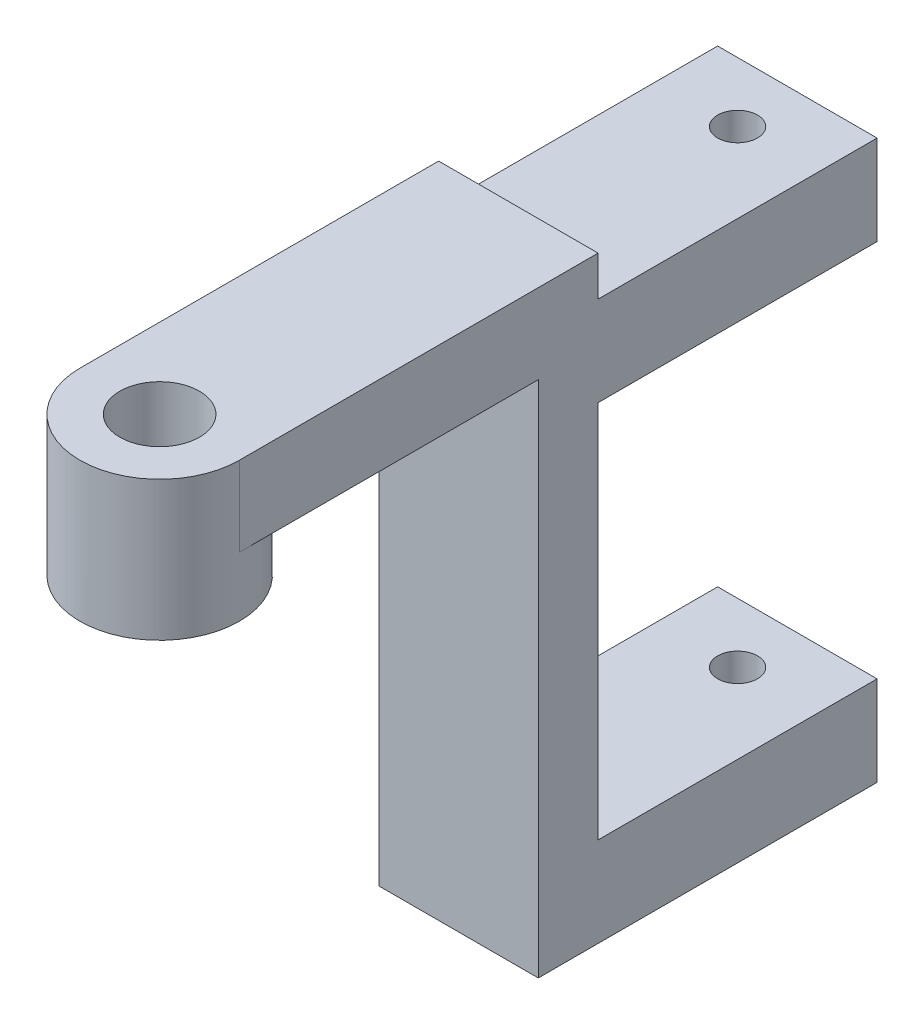
SolidWorks part; units mm, degrees
ref_plane "前视基准面" through (0, 0, 0) normal (0, 0, 1) x (1, 0, 0)
ref_plane "上视基准面" through (0, 0, 0) normal (0, 1, 0) x (1, 0, 0)
ref_plane "右视基准面" through (0, 0, 0) normal (1, 0, 0) x (0, 0, -1)
other "Configuration Table"
sketch "草图1" plane through (0, 0, 0) normal (0, 1, 0) x (1, 0, 0)
  circle A0 centre (0, 0) radius 2
  dimension "D1" = 4
extrude "拉伸-薄壁1" add sketch "草图1" along normal blind 3 thin
sketch "草图2" plane through (0, 3, 0) normal (0, 1, 0) x (1, 0, 0)
  circle A0 centre (0, 0) radius 4
  circle A1 centre (0, 0) radius 4
  circle A2 centre (0, 0) radius 4
  circle M2 centre (0, 0) radius 4
  circle M3 centre (0, 0) radius 2
  dimension "D1" = 0
extrude "凸台-拉伸1" add sketch "草图2" along normal blind 2 contours M2 M3 | M3
sketch "草图3" plane through (0, 5, 0) normal (0, 1, 0) x (1, 0, 0)
  line L1 (-4, 15) -> (4, 15)
  line L2 (-4, 15) -> (-4, 0)
  line L3 (-4, 0) -> (4, 0)
  line L4 (4, 15) -> (4, 0)
  circle A1 centre (0, 0) radius 4
  circle A2 centre (0, 0) radius 4
  circle M6 centre (0, 0) radius 4
  dimension "D2" = 15
  dimension "D1" = 0
extrude "凸台-拉伸2" add sketch "草图3" along normal blind 2 and the other way blind 2 contours L3 M6 | L3 M6 | L4 L1 L2 M6
sketch "草图4" plane through (0, 0, -15) normal (0, 0, -1) x (-1, 0, 0)
  line L1 (-4, 7) -> (4, 7)
  line L2 (-4, 7) -> (-4, -23)
  line L3 (-4, -23) -> (4, -23)
  line L4 (4, 3) -> (4, 7)
  line L5 (4, 7) -> (-4, 7)
  line L6 (-4, 7) -> (-4, 3)
  line L7 (-4, 3) -> (4, 3)
  line L8 (4, 3) -> (4, 7)
  line L9 (4, 7) -> (-4, 7)
  line L10 (-4, 7) -> (-4, 3)
  line L11 (-4, 3) -> (4, 3)
  line L12 (4, 7) -> (4, -23)
  line M9 (4, 3) -> (4, 7)
  line M10 (4, 7) -> (-4, 7)
  line M11 (-4, 7) -> (-4, 3)
  line M12 (-4, 3) -> (4, 3)
  dimension "D2" = 30
  dimension "D1" = 0
extrude "凸台-拉伸3" add sketch "草图4" along normal blind 3 contours L12 L2 L3 M12 | M12 M9 M10 M11
sketch "草图5" plane through (0, 0, -18) normal (0, 0, -1) x (-1, 0, 0)
  line L0 (-16.8506, -9) -> (14.6334, -9) construction
  line L2 (-9.5, 0.5) -> (9.5, 0.5)
  line L3 (-9.5, 0.5) -> (-9.5, -18.5)
  line L4 (4, -23) -> (4, 7)
  line L5 (4, 7) -> (-4, 7)
  line L6 (-4, 7) -> (-4, -23)
  line L7 (-4, -23) -> (4, -23)
  line L8 (4, -23) -> (4, 7)
  line L9 (4, 7) -> (-4, 7)
  line L10 (-4, 7) -> (-4, -23)
  line L11 (-4, -23) -> (4, -23)
  line L12 (-9.5, -18.5) -> (9.5, -18.5)
  line L13 (9.5, 0.5) -> (9.5, -18.5)
  line L14 (-9.5, 0.5) -> (9.5, -18.5) construction
  line L15 (-9.5, -18.5) -> (9.5, 0.5) construction
  line L16 (-4, -23) -> (4, -23)
  line L17 (-4, -23) -> (-4, -18.5)
  line L18 (-4, -18.5) -> (4, -18.5)
  line L19 (4, -23) -> (4, -18.5)
  line L20 (-4, 5) -> (4, 5)
  line L21 (-4, 5) -> (-4, 0.5)
  line L22 (-4, 0.5) -> (4, 0.5)
  line L23 (4, 5) -> (4, 0.5)
  point P6 (0, -9)
  line M14 (4, -23) -> (4, 7)
  line M17 (-4, -23) -> (4, -23)
  dimension "D2" = 16
  dimension "D3" = 19
  dimension "D4" = 19
  dimension "D5" = 4.5
  dimension "D6" = 4.5
  dimension "D1" = 0
extrude "凸台-拉伸4" add sketch "草图5" along normal blind 14 contours L20 L10 L2 M14 | L12 L10 M17 M14
sketch "草图6" plane through (0, 0.5, 0) normal (0, -1, 0) x (1, 0, 0)
  line L0 (0, -11.1975) -> (0, -37.2216) construction
  line L4 (4, -18) -> (-4, -18)
  line L5 (-4, -18) -> (-4, -32)
  line L6 (-4, -32) -> (4, -32)
  line L7 (4, -32) -> (4, -18)
  line L8 (4, -18) -> (-4, -18)
  line L9 (-4, -18) -> (-4, -32)
  line L10 (-4, -32) -> (4, -32)
  line L11 (4, -32) -> (4, -18)
  circle A0 centre (0, -29) radius 1
  dimension "D3" = 2
  dimension "D2" = 11
  dimension "D1" = 0
extrude "切除-拉伸1" cut sketch "草图6" against normal through all and the other way blind 26 contours A0
sketch "草图7" plane through (0, 7, 0) normal (0, 1, 0) x (1, 0, 0)
  line L3 (4, 0) -> (4, 18)
  line L4 (4, 18) -> (-4, 18)
  line L5 (-4, 18) -> (-4, 0)
  line L6 (4, 0) -> (4, 18)
  line L7 (4, 18) -> (-4, 18)
  line L8 (-4, 18) -> (-4, 0)
  circle A0 centre (0, 0) radius 2
  arc A1 (-4, 0) -> (4, 0) centre (0, 0) ccw
  arc A2 (-4, 0) -> (4, 0) centre (0, 0) ccw
  dimension "D2" = 4
  dimension "D1" = 0
extrude "切除-拉伸2" cut sketch "草图7" against normal offset from surface (3 mm away) 1 contours A0 up to face at (0, 3, 2)
sketch "草图8" plane through (0, 4, 0) normal (0, 1, 0) x (1, 0, 0)
  circle A0 centre (0, 0) radius 0.5
  circle A1 centre (0, 0) radius 2
  circle A2 centre (0, 0) radius 2
  dimension "D2" = 1
  dimension "D1" = 0
extrude "切除-拉伸3" cut sketch "草图8" against normal up to next contours A0
